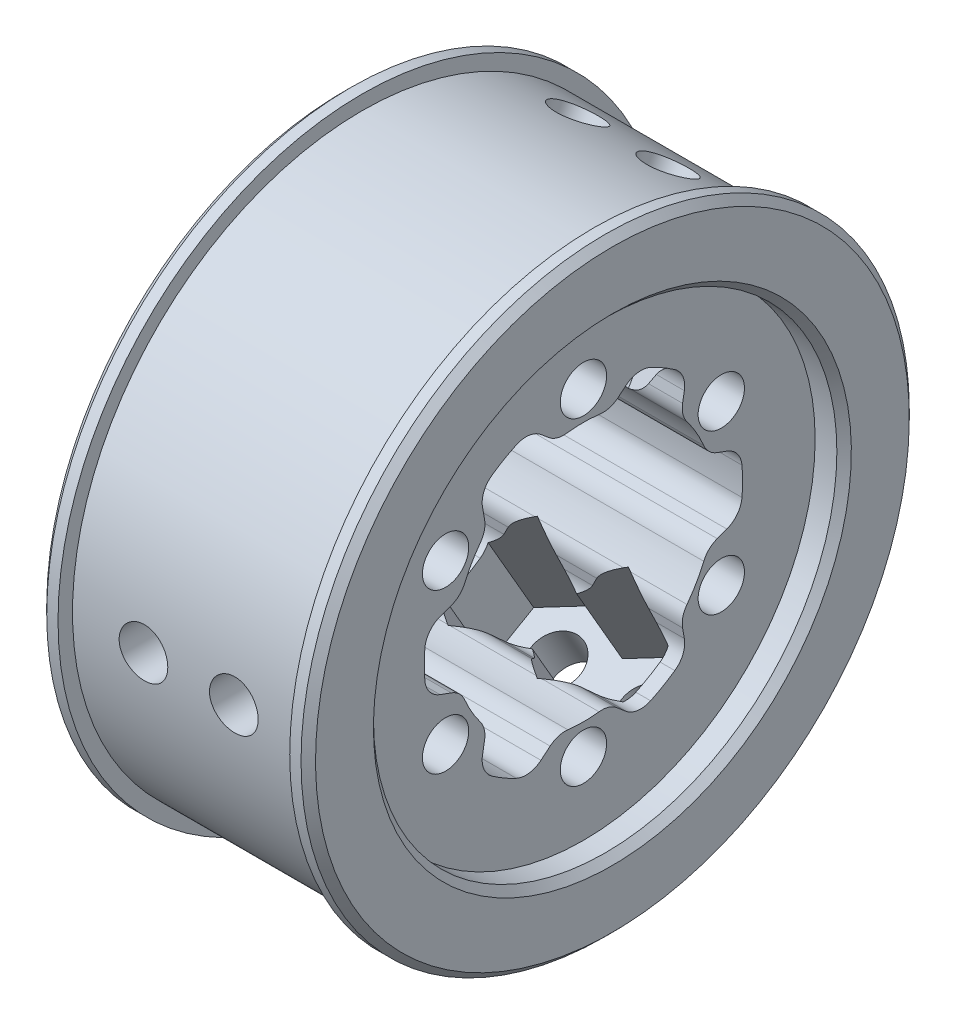
SolidWorks part; units mm, degrees
ref_plane "Front Plane" through (0, 0, 0) normal (0, 0, 1) x (1, 0, 0)
ref_plane "Top Plane" through (0, 0, 0) normal (0, 1, 0) x (1, 0, 0)
ref_plane "Right Plane" through (0, 0, 0) normal (1, 0, 0) x (0, 0, -1)
sketch "Sketch1" plane through (0, 0, 0) normal (0, 0, 1) x (1, 0, 0)
  line L0 (0, 0) -> (0, 31.75)
  line L1 (0, 31.75) -> (12.7, 31.75)
  line L2 (12.7, 31.75) -> (12.7, 33.3375)
  line L3 (12.7, 33.3375) -> (14.732, 33.3375)
  line L4 (14.732, 33.3375) -> (14.732, 0)
  line L5 (14.732, 0) -> (0, 0)
  dimension "D1" = 12.7
  dimension "D2" = 2.032
  dimension "D3" = 1.5875
  dimension "D4" = 31.75
revolve "Revolve1" add sketch "Sketch1" angle 360 about L5
sketch "Sketch2" plane through (14.732, 0, 0) normal (1, 0, 0) x (0, 0, -1)
  line L0 (14.6656, 4.0824) -> (15.7207, 3.6983)
  line L1 (14.6656, -4.0824) -> (15.7207, -3.6983)
  line L2 (0, 0) -> (25.6394, 0) construction
  line L3 (3.6486, -14.6171) -> (4.6575, -15.4637)
  line L4 (10.8682, -10.6596) -> (11.0632, -11.7654)
  line L5 (-10.8345, -10.4683) -> (-11.0632, -11.7654)
  line L6 (-3.6486, -14.6171) -> (-4.6575, -15.4637)
  line L7 (-14.4831, 4.1488) -> (-15.7207, 3.6983)
  line L8 (-14.4831, -4.1488) -> (-15.7207, -3.6983)
  line L9 (-3.7974, 14.7419) -> (-4.6575, 15.4637)
  line L10 (-10.8345, 10.4683) -> (-11.0632, 11.7654)
  line L11 (10.8682, 10.6596) -> (11.0632, 11.7654)
  line L12 (3.7974, 14.7419) -> (4.6575, 15.4637)
  circle A0 centre (0, 0) radius 17.4498 construction
  circle A1 centre (0, 17.4498) radius 2.54
  circle A2 centre (15.112, 8.7249) radius 2.54
  circle A3 centre (15.112, -8.7249) radius 2.54
  circle A4 centre (0, -17.4498) radius 2.54
  circle A5 centre (-15.112, -8.7249) radius 2.54
  circle A6 centre (-15.112, 8.7249) radius 2.54
  circle A7 centre (0, 0) radius 14.2875 construction
  arc A9 (17.3822, 1.5349) -> (17.3822, -1.5349) centre (0, 0) cw
  arc A11 (10.0204, -14.2859) -> (7.3618, -15.8209) centre (0, 0) cw
  arc A12 (-7.3618, -15.8209) -> (-10.0204, -14.2859) centre (0, 0) cw
  arc A13 (-17.3822, -1.5349) -> (-17.3822, 1.5349) centre (0, 0) cw
  arc A14 (-10.0204, 14.2859) -> (-7.3618, 15.8209) centre (0, 0) cw
  arc A15 (7.3618, 15.8209) -> (10.0204, 14.2859) centre (0, 0) cw
  arc A16 (11.3516, -8.6761) -> (13.1895, -5.4927) centre (0, 0) ccw
  arc A18 (-1.709, -14.0414) -> (1.709, -14.0414) centre (0, 0) ccw
  arc A19 (-13.0148, -5.5407) -> (-11.3057, -8.5008) centre (0, 0) ccw
  arc A20 (-11.3057, 8.5008) -> (-13.0148, 5.5407) centre (0, 0) ccw
  arc A21 (1.8379, 14.1688) -> (-1.8379, 14.1688) centre (0, 0) ccw
  arc A22 (13.1895, 5.4927) -> (11.3516, 8.6761) centre (0, 0) ccw
  arc A23 (13.1895, 5.4927) -> (14.6656, 4.0824) centre (15.5343, 6.4692) ccw
  arc A24 (11.3516, 8.6761) -> (10.8682, 10.6596) centre (13.3696, 10.2185) cw
  arc A25 (11.0632, 11.7654) -> (10.0204, 14.2859) centre (8.5618, 12.2065) ccw
  arc A26 (7.3618, 15.8209) -> (4.6575, 15.4637) centre (6.2902, 13.518) ccw
  arc A27 (3.7974, 14.7419) -> (1.8379, 14.1688) centre (2.1647, 16.6877) cw
  arc A28 (-1.8379, 14.1688) -> (-3.7974, 14.7419) centre (-2.1647, 16.6877) cw
  arc A29 (-4.6575, 15.4637) -> (-7.3618, 15.8209) centre (-6.2902, 13.518) ccw
  arc A30 (-10.0204, 14.2859) -> (-11.0632, 11.7654) centre (-8.5618, 12.2065) ccw
  arc A31 (-10.8345, 10.4683) -> (-11.3057, 8.5008) centre (-13.3359, 10.0272) cw
  arc A32 (-13.0148, 5.5407) -> (-14.4831, 4.1488) centre (-15.3518, 6.5356) cw
  arc A33 (-15.7207, 3.6983) -> (-17.3822, 1.5349) centre (-14.852, 1.3115) ccw
  arc A34 (-17.3822, -1.5349) -> (-15.7207, -3.6983) centre (-14.852, -1.3115) ccw
  arc A35 (-14.4831, -4.1488) -> (-13.0148, -5.5407) centre (-15.3518, -6.5356) cw
  arc A36 (-11.3057, -8.5008) -> (-10.8345, -10.4683) centre (-13.3359, -10.0272) cw
  arc A37 (-11.0632, -11.7654) -> (-10.0204, -14.2859) centre (-8.5618, -12.2065) ccw
  arc A38 (-7.3618, -15.8209) -> (-4.6575, -15.4637) centre (-6.2902, -13.518) ccw
  arc A39 (-3.6486, -14.6171) -> (-1.709, -14.0414) centre (-2.0159, -16.5628) cw
  arc A40 (1.709, -14.0414) -> (3.6486, -14.6171) centre (2.0159, -16.5628) cw
  arc A41 (4.6575, -15.4637) -> (7.3618, -15.8209) centre (6.2902, -13.518) ccw
  arc A42 (10.0204, -14.2859) -> (11.0632, -11.7654) centre (8.5618, -12.2065) ccw
  arc A43 (10.8682, -10.6596) -> (11.3516, -8.6761) centre (13.3696, -10.2185) cw
  arc A44 (13.1895, -5.4927) -> (14.6656, -4.0824) centre (15.5343, -6.4692) cw
  arc A45 (15.7207, -3.6983) -> (17.3822, -1.5349) centre (14.852, -1.3115) ccw
  arc A46 (17.3822, 1.5349) -> (15.7207, 3.6983) centre (14.852, 1.3115) ccw
  point P18 (0, 0)
  point P45 (0, 0)
  point P52 (13.5661, 4.4825)
  point P61 (2.9011, 13.9899)
  point P92 (13.5661, -4.4825)
  point P95 (17.1585, -3.175)
  point P98 (17.1585, 3.175)
  dimension "D1" = 34.8996
  dimension "D2" = 5.08
  dimension "D4" = 28.575
  dimension "D5" = 20
  dimension "D7" = 6.35
  dimension "D9" = 2.54
  dimension "D10" = 2.54
  dimension "D6" = 20
  dimension "D3" = 6
  dimension "D8" = 6
mirror "Mirror3" about plane through (0, 0, 0) normal (-1, 0, 0) of "Revolve1"
extrude "Cut-Extrude3" cut sketch "Sketch2" against normal through all
sketch "Sketch3" plane through (14.732, 0, 0) normal (1, 0, 0) x (0, 0, -1)
  circle A0 centre (0, 0) radius 25.4
  dimension "D1" = 50.8
extrude "Cut-Extrude4" cut sketch "Sketch3" against normal blind 3.175
sketch "Sketch4" plane through (-14.732, 0, 0) normal (-1, 0, 0) x (0, 0, 1)
  circle A0 centre (0, 0) radius 25.4
  dimension "D1" = 50.8
extrude "Cut-Extrude5" cut sketch "Sketch4" against normal blind 3.048 contours A0
chamfer "Chamfer1" distance 0.7937 angle 45 4 edges at (-14.732, -25.4, 0) (-14.732, 33.3375, 0) (14.732, 33.3375, 0) (14.732, 25.4, 0)
ref_plane "Plane2" through (0, 0, 17.3822) normal (0, 0, 1) x (1, 0, 0)
ref_plane "Plane3" through (0, -15.0534, 8.6911) normal (0, -0.866, 0.5) x (-1, 0, 0)
sketch "Sketch7" plane through (0, 0, 17.3822) normal (0, 0, 1) x (1, 0, 0)
  line L1 (-4.9213, 5.6092) -> (-9.779, 2.8046)
  line L2 (-9.779, 2.8046) -> (-9.779, -2.8046)
  line L3 (-9.779, -2.8046) -> (-4.9213, -5.6092)
  line L4 (-4.9213, -5.6092) -> (-0.0635, -2.8046)
  line L6 (-0.0635, 2.8046) -> (-4.9213, 5.6092)
  line L7 (4.9848, 5.7192) -> (-0.0635, 2.8046)
  line L9 (-0.0635, -2.8046) -> (4.9848, -5.7192)
  line L10 (4.9848, -5.7192) -> (9.9378, -2.8596)
  line L11 (9.9378, -2.8596) -> (9.9377, 2.8596)
  line L12 (9.9377, 2.8596) -> (4.9848, 5.7192)
  line L13 (-11.684, 1.5349) -> (-11.684, -1.5349) construction
  line L14 (11.557, -1.5349) -> (-11.684, -1.5349) construction
  line L15 (-0.0635, -3.0186) -> (-0.0635, 2.7006) [skipped]
  line L16 (0.0318, 2.8596) -> (0.0318, -2.8596) [skipped]
  circle A0 centre (-4.9213, 0) radius 4.8577 construction
  circle A1 centre (4.9848, 0) radius 4.953 construction
  point P12 (-0.0635, -1.5349)
  point P23 (-11.684, 0)
  dimension "D1" = 9.906
  dimension "D2" = 9.906
extrude "Cut-Extrude6" cut sketch "Sketch7" along normal blind 14.605 from offset 5.08 offset against normal yes
sketch "Sketch10" plane through (0, 0, 26.9072) normal (0, 0, -1) x (-1, 0, 0)
  line L0 (-4.9848, 5.7192) -> (-4.9848, -5.7192) construction
  line L1 (4.9213, 5.6092) -> (4.9213, -5.6092) construction
  circle A0 centre (-4.9848, 0) radius 2.667
  circle A1 centre (4.9213, 0) radius 2.667
  dimension "D1" = 5.334
extrude "Cut-Extrude9" cut sketch "Sketch10" against normal through all
ref_plane "Plane4" through (0, -7.0207, 12.1603) normal (0, -0.5, 0.866) x (1, 0, 0)
sketch "Sketch11" plane through (0, -21.2872, -2.1063) normal (0, 0.866, -0.5) x (1, 0, 0)
  line L0 (11.6525, -12.4677) -> (-11.6712, -12.4677) construction
  line L4 (-12.7, -44.2177) -> (-12.7, 19.2823) construction
  line L5 (12.7, 19.2823) -> (12.7, -44.2177) construction
  circle A0 centre (-7.9375, -6.1177) radius 1.0922
  circle A1 centre (-7.9375, -18.8177) radius 1.0922
  circle A2 centre (7.9375, -18.8177) radius 1.0922
  circle A3 centre (7.9375, -6.1177) radius 1.0922
  point P6 (7.9375, -20.9685)
  point P7 (7.9375, -9.5198)
  point P10 (-7.9375, -20.9685)
  point P11 (-7.9375, -20.9685)
  point P14 (0, 0)
  point P15 (0, 0)
  point P20 (0, 0)
  dimension "D1" = 2.1844
  dimension "D2" = 4.7625
  dimension "D3" = 4.7625
  dimension "D5" = 6.35
  dimension "D6" = 6.35
pattern_circular "CirPattern2" count 3 every 120 about axis through (0, 0, 0) along (1, 0, 0) of "Cut-Extrude9", "Cut-Extrude6"
extrude "Cut-Extrude10" cut sketch "Sketch11" against normal through all
ref_plane "Plane5" through (0, -1.5315, 0.8936) normal (0, -0.8637, 0.504) x (-1, 0, 0)
